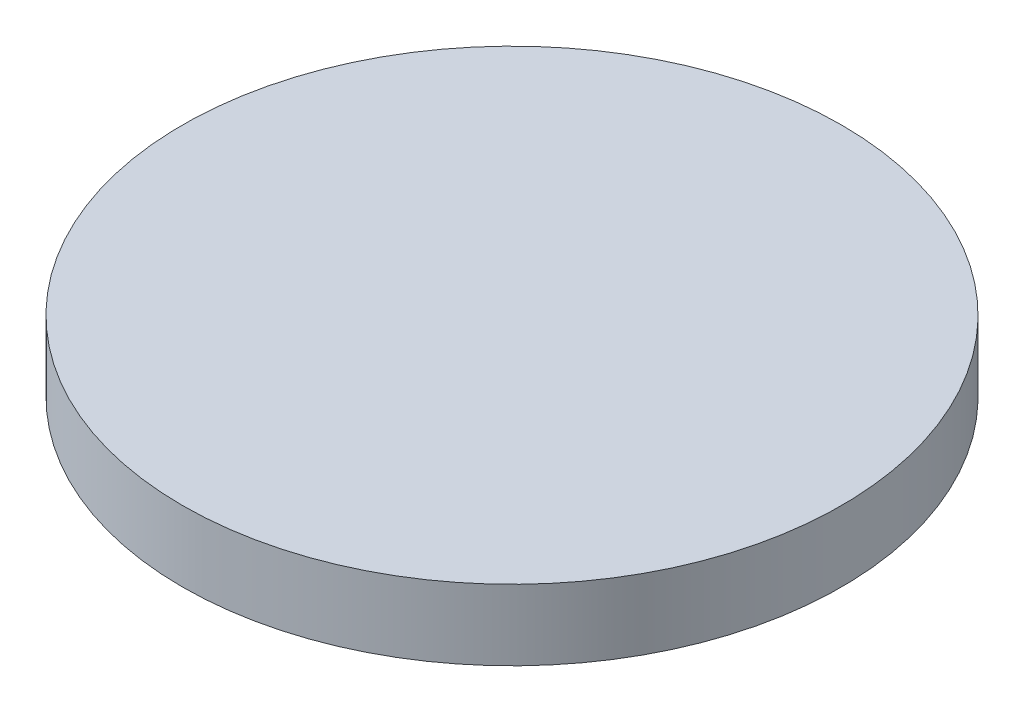
SolidWorks part; units mm, degrees
material "6063-O"
ref_plane "Front Plane" through (0, 0, 0) normal (0, 0, 1) x (1, 0, 0)
ref_plane "Top Plane" through (0, 0, 0) normal (0, 1, 0) x (1, 0, 0)
ref_plane "Right Plane" through (0, 0, 0) normal (1, 0, 0) x (0, 0, -1)
sketch "Sketch1" plane through (0, 0, 0) normal (0, 1, 0) x (1, 0, 0)
  circle A0 centre (0, 0) radius 14
  dimension "D1" = 28
extrude "Boss-Extrude1" add sketch "Sketch1" along normal blind 3
sketch "Sketch2" plane through (0, 3, 0) normal (0, 1, 0) x (1, 0, 0)
  circle A0 centre (0, 0) radius 8 construction
  dimension "D1" = 16
sketch "Sketch5" plane through (0, 3, 0) normal (0, 1, 0) x (1, 0, 0)
  circle A0 centre (0, 0) radius 6
  circle A1 centre (0, 0) radius 7.25
  dimension "D1" = 12
  dimension "D2" = 14.5
extrude "Boss-Extrude2" [suppressed] add sketch "Sketch5" along normal blind 0.5 separate body
sketch "Sketch8" plane through (0, 0, 0) normal (0, -1, 0) x (-1, 0, 0)
  circle A0 centre (0, 0) radius 11 construction
  dimension "D1" = 22
hole_wizard "M2.5 Tapped Hole1" [suppressed] positions "Sketch9" profile "Sketch10" tap size "M2.5" standard "ISO"
sketch "Sketch9" plane through (0, 0, 0) normal (0, -1, 0) x (-1, 0, 0)
  circle A0 centre (0, 0) radius 11 construction
  point P0 (0, -11)
sketch "Sketch10" plane through (0, 0, 11) normal (1, 0, 0) x (0, 0, -1)
  line L0 (0, 0) -> (0, 2.5)
  line L1 (0, 2.5) -> (1.025, 2.5)
  line L2 (1.025, 2.5) -> (1.025, 0)
  line L5 (1.025, 0) -> (0, 0)
  line L11 (0, -6.35) -> (0, 107.95) construction
  dimension "Thru Tap Drill Dia." = 2.05
  dimension "Thru Tap Drill Depth" = 2.5
cosmetic thread "Hole Thread2" [suppressed] parameters "D2"=2.5
pattern_circular "CirPattern3" [suppressed] count 8 over 360
cosmetic thread "Cosmetic Thread8" parameters "D2"=2.5
cosmetic thread "Cosmetic Thread9" parameters "D2"=2.5
cosmetic thread "Cosmetic Thread10" parameters "D2"=2.5
cosmetic thread "Cosmetic Thread11" parameters "D2"=2.5
cosmetic thread "Cosmetic Thread12" parameters "D2"=2.5
cosmetic thread "Cosmetic Thread13" parameters "D2"=2.5
cosmetic thread "Cosmetic Thread14" parameters "D2"=2.5
sketch "Sketch18" [suppressed] plane through (0, 3, 0) normal (0, 1, 0) x (1, 0, 0)
  circle A0 centre (0, 0) radius 8 construction
  dimension "D1" = 16
hole_wizard "M2 Tapped Hole1" [suppressed] positions "Sketch19" profile "Sketch20" tap size "M2" standard "ISO"
sketch "Sketch19" [suppressed] plane through (0, 3, 0) normal (0, 1, 0) x (1, 0, 0)
  circle A0 centre (0, 0) radius 8 construction
  point P0 (0, 8)
sketch "Sketch20" plane through (0, 3, -8) normal (1, 0, 0) x (0, 0, 1)
  line L0 (0, 0) -> (0, 3)
  line L1 (0, 3) -> (0.8, 3)
  line L2 (0.8, 3) -> (0.8, 0)
  line L5 (0.8, 0) -> (0, 0)
  line L11 (0, -6.35) -> (0, 107.95) construction
  dimension "Thru Tap Drill Dia." = 1.6
  dimension "Thru Tap Drill Depth" = 3
cosmetic thread "Hole Thread3" [suppressed] parameters "D2"=2
pattern_circular "CirPattern4" [suppressed] count 8 over 360
cosmetic thread "Cosmetic Thread1" parameters "D2"=2.5
cosmetic thread "Cosmetic Thread2" parameters "D2"=2.5
cosmetic thread "Cosmetic Thread3" parameters "D2"=2.5
cosmetic thread "Cosmetic Thread4" parameters "D2"=2.5
cosmetic thread "Cosmetic Thread6" parameters "D2"=2.5
cosmetic thread "Cosmetic Thread7" parameters "D2"=2.5
